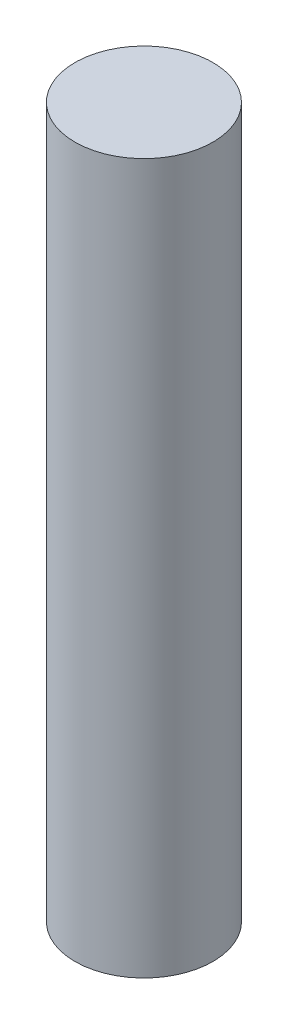
SolidWorks part; units mm, degrees
ref_plane "Front Plane" through (0, 0, 0) normal (0, 0, 1) x (1, 0, 0)
ref_plane "Top Plane" through (0, 0, 0) normal (0, 1, 0) x (1, 0, 0)
ref_plane "Right Plane" through (0, 0, 0) normal (1, 0, 0) x (0, 0, -1)
sketch "Sketch1" plane through (0, 0, 0) normal (0, 1, 0) x (1, 0, 0)
  circle A0 centre (0, 0) radius 2.7781
extrude "Boss-Extrude1" add sketch "Sketch1" along normal blind 28.575
